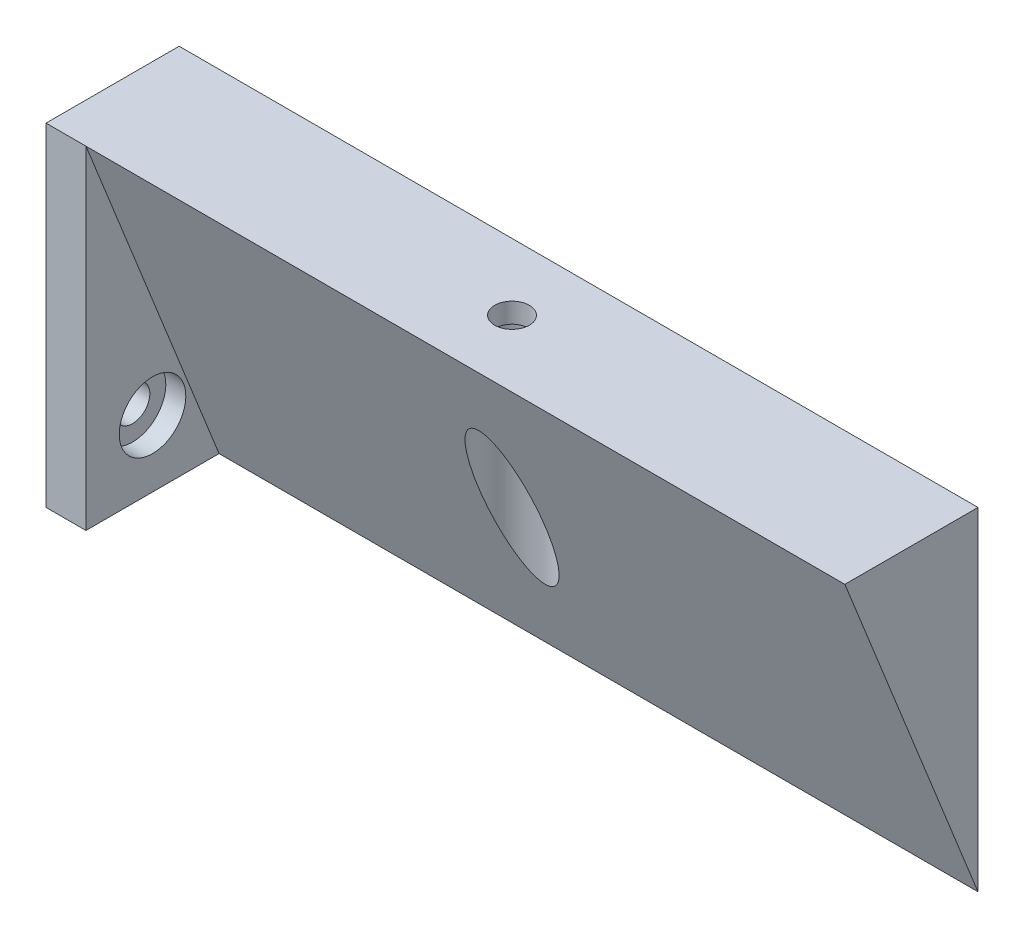
SolidWorks part; units mm, degrees
ref_plane "前视基准面" through (0, 0, 0) normal (0, 0, 1) x (1, 0, 0)
ref_plane "上视基准面" through (0, 0, 0) normal (0, 1, 0) x (1, 0, 0)
ref_plane "右视基准面" through (0, 0, 0) normal (1, 0, 0) x (0, 0, -1)
other "Configuration Table"
sketch "草图1" plane through (0, 0, 0) normal (0, 1, 0) x (1, 0, 0)
  line L1 (0, 0) -> (120, 0)
  line L2 (0, 0) -> (0, 20)
  line L3 (0, 20) -> (120, 20)
  line L4 (120, 0) -> (120, 20)
extrude "凸台-拉伸1" add sketch "草图1" along normal blind 50
sketch "草图2" plane through (0, 0, 0) normal (0, 0, 1) x (1, 0, 0)
  line L1 (0, 0) -> (6, 0)
  line L2 (0, 0) -> (0, -20)
  line L3 (0, -20) -> (6, -20)
  line L4 (6, 0) -> (6, -20)
extrude "凸台-拉伸2" add sketch "草图2" against normal blind 20
sketch "草图3" plane through (120, 0, 0) normal (1, 0, 0) x (0, 0, -1)
  line L0 (0, 50) -> (20, 0)
  line L1 (20, 0) -> (0, 0)
  line L2 (0, 0) -> (0, 50)
extrude "切除-拉伸1" cut sketch "草图3" against normal blind 114 contours L2 L0 L1
sketch "草图4" plane through (6, 0, 0) normal (1, 0, 0) x (0, 0, -1)
  line L4 (20, 0) -> (0, 0)
  line L5 (20, 0) -> (20, -20)
  line L6 (20, -20) -> (0, -20)
  line L7 (0, 0) -> (0, -20)
  circle A0 centre (10, 10) radius 2.6
extrude "切除-拉伸2" cut sketch "草图4" against normal blind 114 contours A0 | L5 L4 L7 L6
sketch "草图5" plane through (6, 0, 0) normal (1, 0, 0) x (0, 0, -1)
  circle A0 centre (10, 10) radius 5
extrude "切除-拉伸3" cut sketch "草图5" against normal blind 3
sketch "草图6" plane through (0, 50, 0) normal (0, 1, 0) x (1, 0, 0)
  line L0 (60, 20) -> (60, 0)
  line L1 (120, 20) -> (0, 20) construction
  line L2 (6, 0) -> (120, 0) construction
  circle A0 centre (60, 10) radius 2.6
extrude "切除-拉伸4" cut sketch "草图6" against normal blind 300 contours L0 A0 | L0 A0
sketch "草图8" plane through (0, 50, 0) normal (0, 1, 0) x (1, 0, 0)
  circle A0 centre (60, 10) radius 5
extrude "切除-拉伸5" cut sketch "草图8" against normal blind 300
sketch "草图9" plane through (0, 50, 0) normal (0, 1, 0) x (1, 0, 0)
  circle A0 centre (60, 10) radius 5
  circle A1 centre (60, 10) radius 2.6
extrude "凸台-拉伸3" add sketch "草图9" against normal blind 3
